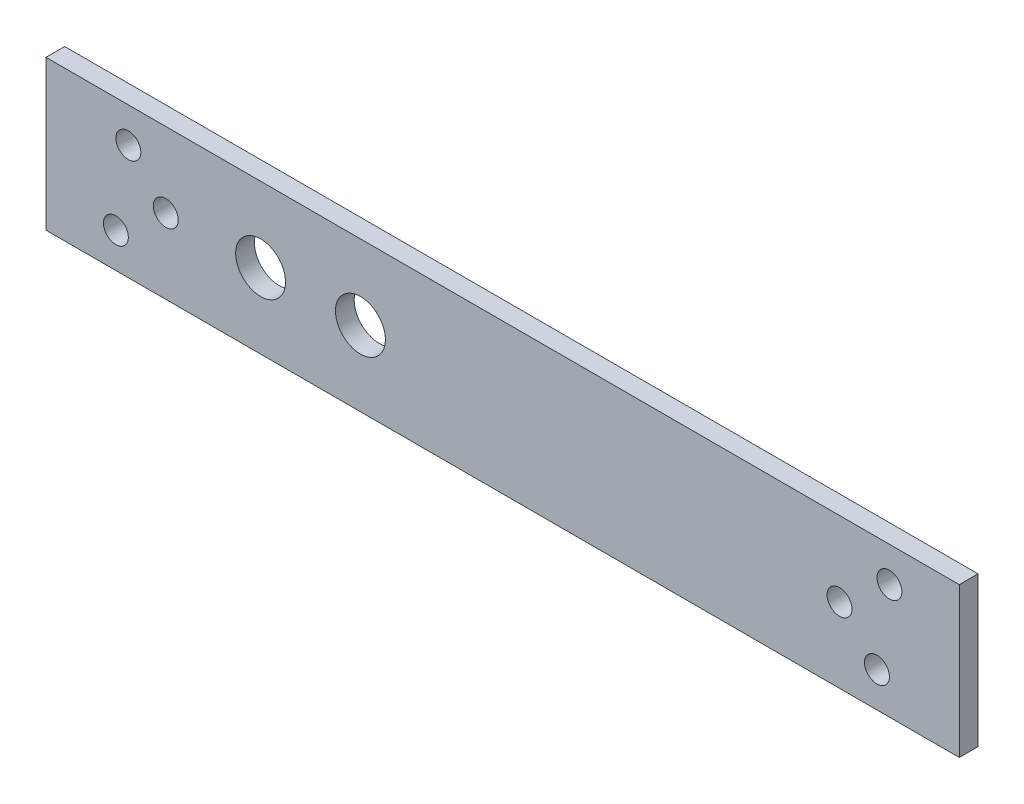
SolidWorks part; units mm, degrees
ref_plane "Front Plane" through (0, 0, 0) normal (0, 0, 1) x (1, 0, 0)
ref_plane "Top Plane" through (0, 0, 0) normal (0, 1, 0) x (1, 0, 0)
ref_plane "Right Plane" through (0, 0, 0) normal (1, 0, 0) x (0, 0, -1)
sketch "Sketch1" plane through (0, 0, 0) normal (0, 0, 1) x (1, 0, 0)
  line L0 (38.1, 38.1) -> (38.1, 0) construction
  line L1 (0, 0) -> (232.41, 0)
  line L2 (0, 0) -> (0, 38.1)
  line L3 (0, 38.1) -> (232.41, 38.1)
  line L4 (232.41, 0) -> (232.41, 38.1)
  line L5 (194.31, 38.1) -> (194.31, 0) construction
  circle A0 centre (30.48, 19.05) radius 3.175
  circle A2 centre (80.01, 19.05) radius 6.35
  circle A3 centre (20.955, 29.21) radius 3.175
  circle A4 centre (17.78, 8.89) radius 3.175
  circle A5 centre (214.63, 29.21) radius 3.175
  circle A6 centre (201.93, 19.05) radius 3.175
  circle A7 centre (211.455, 8.89) radius 3.175
  circle A8 centre (54.61, 19.05) radius 6.35
  point P9 (0, 19.05)
  point P16 (38.1, 19.05)
  dimension "D3" = 6.35
  dimension "D15" = 12.7
  dimension "D1" = 232.41
  dimension "D2" = 38.1
  dimension "D4" = 38.1
  dimension "D5" = 7.62
  dimension "D6" = 177.8
  dimension "D7" = 20.32
  dimension "D8" = 8.89
  dimension "D9" = 8.89
  dimension "D10" = 17.145
  dimension "D11" = 20.32
  dimension "D12" = 17.145
  dimension "D13" = 7.62
  dimension "D14" = 38.1
  dimension "D16" = 25.4
extrude "Boss-Extrude1" add sketch "Sketch1" along normal blind 4.7625
